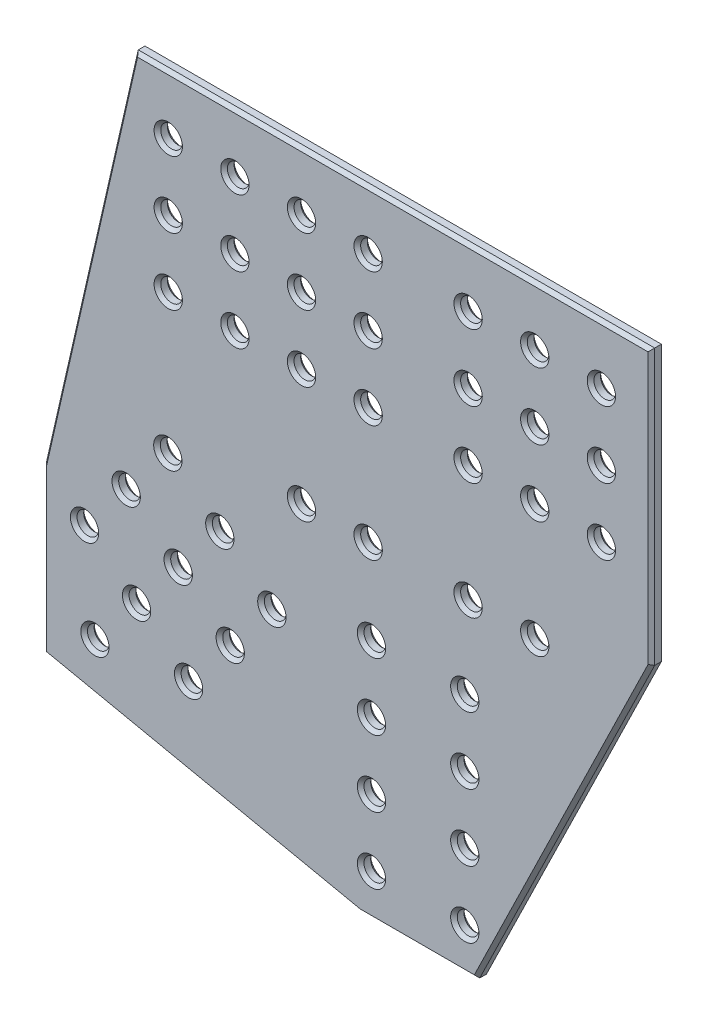
SolidWorks part; units mm, degrees
ref_plane "前视" through (0, 0, 0) normal (0, 0, 1) x (1, 0, 0)
ref_plane "上视" through (0, 0, 0) normal (0, 1, 0) x (1, 0, 0)
ref_plane "右视" through (0, 0, 0) normal (1, 0, 0) x (0, 0, -1)
sketch "草图1" plane through (0, 0, 0) normal (0, 0, 1) x (1, 0, 0)
  line L0 (730, -330) -> (520, -760)
  line L1 (110, 0) -> (730, 0)
  line L2 (0, -482.7866) -> (0, -680)
  line L3 (380, -760) -> (520, -760)
  line L4 (730, 0) -> (730, -330)
  line L5 (0, -482.7866) -> (110, 0)
  line L6 (0, 0) -> (0, 307.009) construction
  line L7 (0, 307.009) -> (0, -942.9561) construction
  line L8 (0, 0) -> (1145.1922, 0) construction
  line L9 (0, -680) -> (380, -760)
  line L10 (450, -1142.7556) -> (450, 165.6874) construction
  line L11 (510, 146.1947) -> (510, -423.4249) construction
  line L12 (-204.6726, -70) -> (986.8145, -70) construction
  line L13 (590, 146.1947) -> (590, -492.189) construction
  line L14 (-204.6726, -230) -> (918.5903, -230) construction
  line L15 (670, 146.1947) -> (670, -470.2598) construction
  line L16 (-204.6726, -150) -> (986.8145, -150) construction
  line L17 (150, 0) -> (150, -387.2631) construction
  line L18 (380, -470) -> (553.1035, -470) construction
  line L19 (250.9676, -370) -> (653.0032, -370) construction
  line L20 (380, -550) -> (553.1035, -550) construction
  line L21 (450, -400) -> (90.1534, -400) construction
  line L22 (380, -630) -> (553.1035, -630) construction
  line L23 (450, -150) -> (249.9573, -399.9658) construction
  line L24 (380, -710) -> (544.4186, -710) construction
  line L25 (249.9573, -399.9658) -> (0, -712.3029) construction
  line L26 (123.5646, -376.7449) -> (331.8306, -543.4161) construction
  line L27 (69.3486, -435.821) -> (277.7181, -602.575) construction
  line L29 (-53.2368, -650.7905) -> (192.5549, -343.6585) construction
  line L30 (506, -447.511) -> (506, -741.3026) construction
  line L31 (0, -482.7866) -> (213.7577, -653.8527) construction
  circle A0 centre (510, -70) radius 13
  circle A1 centre (590, -70) radius 13
  circle A2 centre (670, -70) radius 13
  circle A3 centre (510, -150) radius 13
  circle A4 centre (590, -150) radius 13
  circle A5 centre (670, -150) radius 13
  circle A6 centre (510, -230) radius 13
  circle A7 centre (590, -230) radius 13
  circle A8 centre (670, -230) radius 13
  circle A9 centre (230, -230) radius 13
  circle A10 centre (310, -230) radius 13
  circle A11 centre (390, -230) radius 13
  circle A12 centre (230, -150) radius 13
  circle A13 centre (310, -150) radius 13
  circle A14 centre (390, -150) radius 13
  circle A15 centre (230, -70) radius 13
  circle A16 centre (310, -70) radius 13
  circle A17 centre (390, -70) radius 13
  circle A18 centre (150, -70) radius 13
  circle A19 centre (150, -150) radius 13
  circle A20 centre (150, -230) radius 13
  circle A21 centre (590, -370) radius 13
  circle A22 centre (510, -370) radius 13
  circle A23 centre (390, -370) radius 13
  circle A24 centre (310, -370) radius 13
  circle A25 centre (506, -470) radius 13
  circle A26 centre (506, -550) radius 13
  circle A27 centre (506, -630) radius 13
  circle A28 centre (506, -710) radius 13
  circle A29 centre (394, -710) radius 13
  circle A30 centre (394, -630) radius 13
  circle A31 centre (394, -550) radius 13
  circle A32 centre (394, -470) radius 13
  circle A33 centre (149.4794, -397.4841) radius 13
  circle A34 centre (99.4931, -459.945) radius 13
  circle A35 centre (49.5068, -522.406) radius 13
  circle A36 centre (61.9815, -634.8532) radius 13
  circle A37 centre (111.9678, -572.3923) radius 13
  circle A38 centre (161.9541, -509.9313) radius 13
  circle A39 centre (211.9403, -447.4703) radius 13
  circle A40 centre (174.4287, -622.3785) radius 13
  circle A41 centre (224.415, -559.9176) radius 13
  circle A42 centre (274.4013, -497.4566) radius 13
  point P1 (110, 0)
  point P5 (520, -760)
  point P6 (730, -330)
  point P9 (249.9299, -400)
  point P16 (0, -680)
  point P17 (380, -760)
  point P110 (450, -150)
  point P111 (450, -400)
  point P122 (61.9815, -634.8532)
  dimension "D16" = 26
  dimension "D28" = 26
  dimension "D1" = 760
  dimension "D2" = 730
  dimension "D3" = 210
  dimension "D4" = 430
  dimension "D5" = 110
  dimension "D6" = 320.2
  dimension "D7" = 80
  dimension "D8" = 380
  dimension "D9" = 280
  dimension "D10" = 60
  dimension "D11" = 80
  dimension "D12" = 80
  dimension "D13" = 70
  dimension "D14" = 80
  dimension "D15" = 80
  dimension "D17" = 300
  dimension "D18" = 140
  dimension "D19" = 100
  dimension "D20" = 80
  dimension "D21" = 80
  dimension "D22" = 80
  dimension "D23" = 250
  dimension "D24" = 80
  dimension "D25" = 381
  dimension "D26" = 80
  dimension "D27" = 80
  dimension "D29" = 80
  dimension "D30" = 56
extrude "基体-拉伸" add sketch "草图1" along normal blind 16
chamfer "倒角2" distance 4 angle 45 100 edges at (381, -470, 0) (211.415, -559.9176, 0) (224.9403, -447.4703, 0) (124.9678, -572.3923, 0) (62.5068, -522.406, 0) (162.4794, -397.4841, 0) (381, -630, 0) (519, -710, 0) (519, -550, 0) (297, -370, 0) (523, -370, 0) (163, -230, 0) (163, -70, 0) (297, -70, 0) (377, -150, 0) (217, -150, 0) (297, -230, 0) (683, -230, 0) (523, -230, 0) (603, -150, 0) (683, -70, 0) (523, -70, 0) (420, 0, 0) (55, -241.3933, 0) (0, -581.3933, 0) (190, -720, 0) (450, -760, 0) (625, -545, 0) (730, -165, 0) (603, -70, 0) (523, -150, 0) (683, -150, 0) (603, -230, 0) (217, -230, 0) (377, -230, 0) (297, -150, 0) (217, -70, 0) (377, -70, 0) (163, -150, 0) (603, -370, 0) (377, -370, 0) (519, -470, 0) (519, -630, 0) (381, -710, 0) (381, -550, 0) (112.4931, -459.945, 0) (74.9815, -634.8532, 0) (174.9541, -509.9313, 0) (161.4287, -622.3785, 0) (261.4013, -497.4566, 0) (381, -470, 16) (211.415, -559.9176, 16) (224.9403, -447.4703, 16) (124.9678, -572.3923, 16) (62.5068, -522.406, 16) (162.4794, -397.4841, 16) (381, -630, 16) (519, -710, 16) (519, -550, 16) (297, -370, 16) (523, -370, 16) (163, -230, 16) (163, -70, 16) (297, -70, 16) (377, -150, 16) (217, -150, 16) (297, -230, 16) (683, -230, 16) (523, -230, 16) (603, -150, 16) (683, -70, 16) (523, -70, 16) (625, -545, 16) (450, -760, 16) (190, -720, 16) (0, -581.3933, 16) (55, -241.3933, 16) (420, 0, 16) (730, -165, 16) (603, -70, 16) (523, -150, 16) (683, -150, 16) (603, -230, 16) (217, -230, 16) (377, -230, 16) (297, -150, 16) (217, -70, 16) (377, -70, 16) (163, -150, 16) (603, -370, 16) (377, -370, 16) (519, -470, 16) (519, -630, 16) (381, -710, 16) (381, -550, 16) (112.4931, -459.945, 16) (74.9815, -634.8532, 16) (174.9541, -509.9313, 16) (161.4287, -622.3785, 16) (261.4013, -497.4566, 16)
